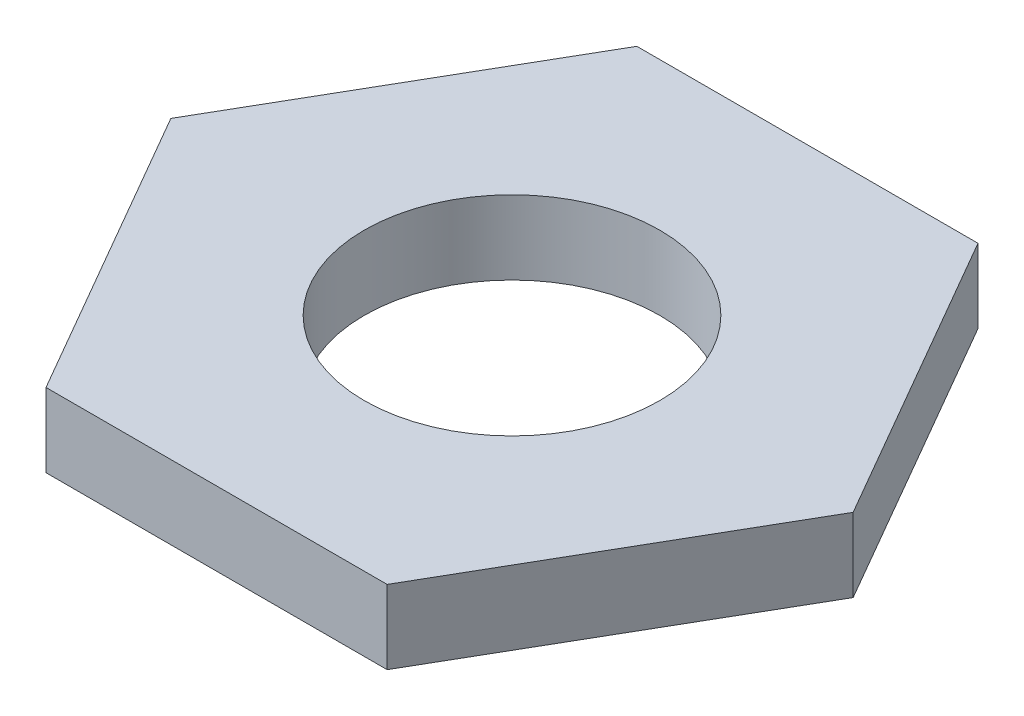
SolidWorks part; units mm, degrees
ref_plane "Front Plane" through (0, 0, 0) normal (0, 0, 1) x (1, 0, 0)
ref_plane "Top Plane" through (0, 0, 0) normal (0, 1, 0) x (1, 0, 0)
ref_plane "Right Plane" through (0, 0, 0) normal (1, 0, 0) x (0, 0, -1)
sketch "Sketch1" plane through (0, 0, 0) normal (0, 1, 0) x (1, 0, 0)
  line L1 (2.3094, 4) -> (-2.3094, 4)
  line L2 (-2.3094, 4) -> (-4.6188, 0)
  line L3 (-4.6188, 0) -> (-2.3094, -4)
  line L4 (-2.3094, -4) -> (2.3094, -4)
  line L5 (2.3094, -4) -> (4.6188, 0)
  line L6 (4.6188, 0) -> (2.3094, 4)
  circle A0 centre (0, 0) radius 4 construction
  circle A1 centre (0, 0) radius 2
  dimension "D2" = 4
  dimension "D1" = 8
extrude "Boss-Extrude1" add sketch "Sketch1" along normal blind 1
